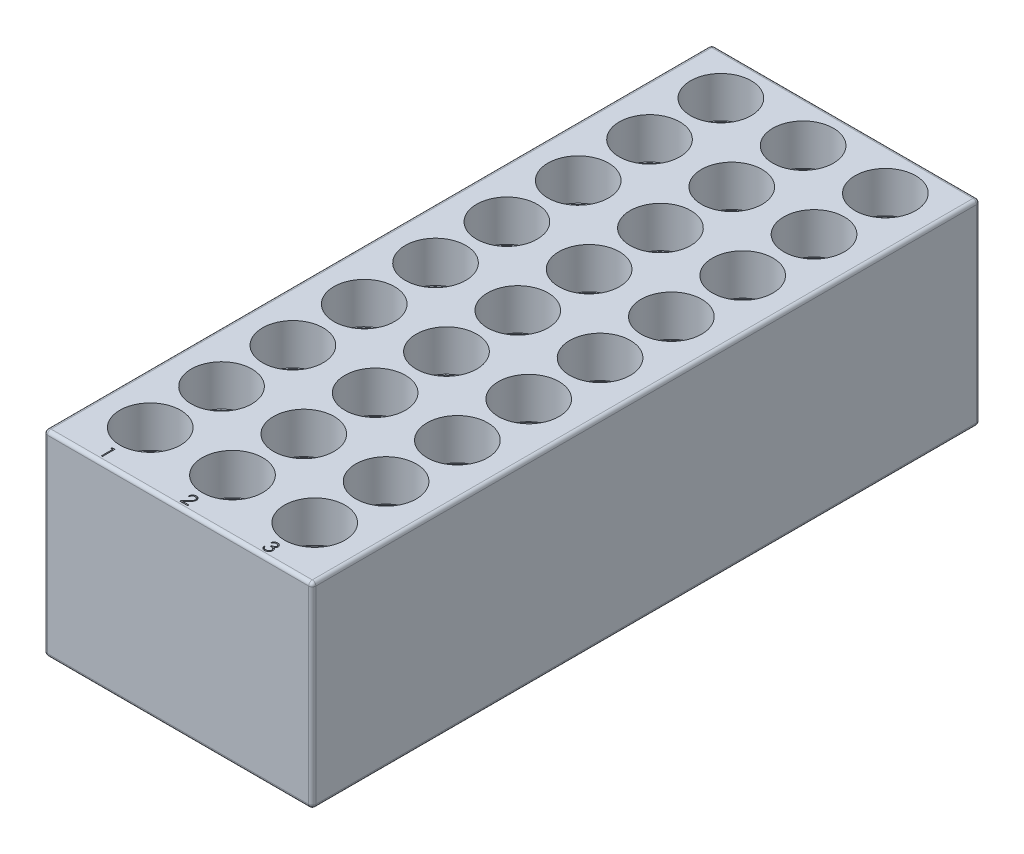
SolidWorks part; units mm, degrees
ref_plane "Front Plane" through (0, 0, 0) normal (0, 0, 1) x (1, 0, 0)
ref_plane "Top Plane" through (0, 0, 0) normal (0, 1, 0) x (1, 0, 0)
ref_plane "Right Plane" through (0, 0, 0) normal (1, 0, 0) x (0, 0, -1)
sketch "Sketch1" plane through (0, 0, 0) normal (0, 1, 0) x (1, 0, 0)
  line L0 (-23.0625, 61.625) -> (-37.625, 61.625) construction
  line L1 (37.625, -93.625) -> (-37.625, -93.625)
  line L2 (37.625, -93.625) -> (37.625, 93.625)
  line L3 (37.625, 93.625) -> (-37.625, 93.625)
  line L4 (-37.625, -93.625) -> (-37.625, 93.625)
  line L5 (37.625, -93.625) -> (-37.625, 93.625) construction
  line L6 (37.625, 93.625) -> (-37.625, -93.625) construction
  line L7 (-23.0625, 81.625) -> (-37.625, 81.625) construction
  line L8 (-23.0625, 81.625) -> (-23.0625, 93.625) construction
  line L9 (23.0625, 81.625) -> (37.625, 81.625) construction
  line L10 (-8.5, 81.625) -> (-23.0625, 81.625) construction
  circle A0 centre (-23.0625, 81.625) radius 8.5
  circle A1 centre (0, 81.625) radius 8.5
  circle A2 centre (23.0625, 81.625) radius 8.5
  circle A6 centre (-23.0625, 61.625) radius 8.5
  circle A7 centre (0, 61.625) radius 8.5
  circle A8 centre (23.0625, 61.625) radius 8.5
  circle A12 centre (-23.0625, 41.625) radius 8.5
  circle A13 centre (0, 41.625) radius 8.5
  circle A14 centre (23.0625, 41.625) radius 8.5
  circle A18 centre (-23.0625, 21.625) radius 8.5
  circle A19 centre (0, 21.625) radius 8.5
  circle A20 centre (23.0625, 21.625) radius 8.5
  circle A24 centre (-23.0625, 1.625) radius 8.5
  circle A25 centre (0, 1.625) radius 8.5
  circle A26 centre (23.0625, 1.625) radius 8.5
  circle A30 centre (-23.0625, -18.375) radius 8.5
  circle A31 centre (0, -18.375) radius 8.5
  circle A32 centre (23.0625, -18.375) radius 8.5
  circle A36 centre (-23.0625, -38.375) radius 8.5
  circle A37 centre (0, -38.375) radius 8.5
  circle A38 centre (23.0625, -38.375) radius 8.5
  circle A42 centre (-23.0625, -58.375) radius 8.5
  circle A43 centre (0, -58.375) radius 8.5
  circle A44 centre (23.0625, -58.375) radius 8.5
  circle A48 centre (-23.0625, -78.375) radius 8.5
  circle A49 centre (0, -78.375) radius 8.5
  circle A50 centre (23.0625, -78.375) radius 8.5
  point P0 (0, 0)
  dimension "D1" = 17
  dimension "D3" = 20
  dimension "D5" = 12
  dimension "D7" = 187.25
  dimension "D9" = 75.25
  dimension "D2" = 3
  dimension "D6" = 9
extrude "Boss-Extrude1" add sketch "Sketch1" along normal blind 50
sketch "Sketch3" plane through (0, 0, 0) normal (0, -1, 0) x (1, 0, 0)
  line L1 (-37.625, 93.625) -> (37.625, 93.625)
  line L2 (-37.625, 93.625) -> (-37.625, -93.625)
  line L3 (-37.625, -93.625) -> (37.625, -93.625)
  line L4 (37.625, 93.625) -> (37.625, -93.625)
extrude "Boss-Extrude2" add sketch "Sketch3" along normal blind 5
sketch "Sketch4" plane through (0, 50, 0) normal (0, 1, 0) x (1, 0, 0)
  text T0 "1               2               3"
  point P1 (0, 0)
  point P2 (0, 0)
  point P3 (0, 0)
shell "Shell3" [suppressed] thickness 0.1
sketch "Sketch5" plane through (0, 0, 0) normal (0, 1, 0) x (1, 0, 0)
  line L4 (-37.625, -93.625) -> (37.625, -93.625)
  line L5 (-37.625, 93.625) -> (-37.625, -93.625)
  line L6 (37.625, 93.625) -> (-37.625, 93.625)
  line L7 (37.625, -93.625) -> (37.625, 93.625)
  line L8 (-37.625, -93.625) -> (37.625, -93.625)
  line L9 (-37.625, 93.625) -> (-37.625, -93.625)
  line L10 (37.625, 93.625) -> (-37.625, 93.625)
  line L11 (37.625, -93.625) -> (37.625, 93.625)
  circle A0 centre (-23.0625, 81.625) radius 8.1
  circle A1 centre (-0.0625, 81.625) radius 8.1
  circle A2 centre (22.9375, 81.625) radius 8.1
  circle A3 centre (-0.0625, 61.625) radius 8.1
  circle A4 centre (22.9375, 61.625) radius 8.1
  circle A5 centre (-0.0625, 41.625) radius 8.1
  circle A6 centre (22.9375, 41.625) radius 8.1
  circle A7 centre (-0.0625, 21.625) radius 8.1
  circle A8 centre (22.9375, 21.625) radius 8.1
  circle A9 centre (-0.0625, 1.625) radius 8.1
  circle A10 centre (22.9375, 1.625) radius 8.1
  circle A11 centre (-0.0625, -18.375) radius 8.1
  circle A12 centre (22.9375, -18.375) radius 8.1
  circle A13 centre (-0.0625, -38.375) radius 8.1
  circle A14 centre (22.9375, -38.375) radius 8.1
  circle A15 centre (-0.0625, -58.375) radius 8.1
  circle A16 centre (22.9375, -58.375) radius 8.1
  circle A17 centre (-0.0625, -78.375) radius 8.1
  circle A18 centre (22.9375, -78.375) radius 8.1
  circle A19 centre (-23.0625, 61.625) radius 8.1
  circle A20 centre (-23.0625, 41.625) radius 8.1
  circle A21 centre (-23.0625, 21.625) radius 8.1
  circle A22 centre (-23.0625, 1.625) radius 8.1
  circle A23 centre (-23.0625, -18.375) radius 8.1
  circle A24 centre (-23.0625, -38.375) radius 8.1
  circle A25 centre (-23.0625, -58.375) radius 8.1
  circle A26 centre (-23.0625, -78.375) radius 8.1
  circle A28 centre (23.0625, 81.625) radius 8.5
  circle A29 centre (23.0625, 81.625) radius 8.5
  circle A30 centre (0, 81.625) radius 8.5
  circle A31 centre (0, 81.625) radius 8.5
  circle A32 centre (-23.0625, 81.625) radius 8.5
  circle A33 centre (-23.0625, 81.625) radius 8.5
  circle A34 centre (23.0625, 61.625) radius 8.5
  circle A35 centre (23.0625, 61.625) radius 8.5
  circle A36 centre (0, 61.625) radius 8.5
  circle A37 centre (0, 61.625) radius 8.5
  circle A38 centre (-23.0625, 61.625) radius 8.5
  circle A39 centre (-23.0625, 61.625) radius 8.5
  circle A40 centre (-23.0625, 21.625) radius 8.5
  circle A41 centre (-23.0625, 21.625) radius 8.5
  circle A42 centre (23.0625, 41.625) radius 8.5
  circle A43 centre (23.0625, 41.625) radius 8.5
  circle A44 centre (0, 41.625) radius 8.5
  circle A45 centre (0, 41.625) radius 8.5
  circle A46 centre (-23.0625, 41.625) radius 8.5
  circle A47 centre (-23.0625, 41.625) radius 8.5
  circle A48 centre (23.0625, 1.625) radius 8.5
  circle A49 centre (23.0625, 1.625) radius 8.5
  circle A50 centre (0, 1.625) radius 8.5
  circle A51 centre (0, 1.625) radius 8.5
  circle A52 centre (-23.0625, 1.625) radius 8.5
  circle A53 centre (-23.0625, 1.625) radius 8.5
  circle A54 centre (23.0625, 21.625) radius 8.5
  circle A55 centre (23.0625, 21.625) radius 8.5
  circle A56 centre (0, 21.625) radius 8.5
  circle A57 centre (0, 21.625) radius 8.5
  circle A58 centre (23.0625, -18.375) radius 8.5
  circle A59 centre (23.0625, -18.375) radius 8.5
  circle A60 centre (0, -18.375) radius 8.5
  circle A61 centre (0, -18.375) radius 8.5
  circle A62 centre (-23.0625, -18.375) radius 8.5
  circle A63 centre (-23.0625, -18.375) radius 8.5
  circle A64 centre (23.0625, -38.375) radius 8.5
  circle A65 centre (23.0625, -38.375) radius 8.5
  circle A66 centre (0, -38.375) radius 8.5
  circle A67 centre (0, -38.375) radius 8.5
  circle A68 centre (-23.0625, -38.375) radius 8.5
  circle A69 centre (-23.0625, -38.375) radius 8.5
  circle A70 centre (0, -78.375) radius 8.5
  circle A71 centre (0, -78.375) radius 8.5
  circle A72 centre (-23.0625, -78.375) radius 8.5
  circle A73 centre (-23.0625, -78.375) radius 8.5
  circle A74 centre (23.0625, -58.375) radius 8.5
  circle A75 centre (23.0625, -58.375) radius 8.5
  circle A76 centre (0, -58.375) radius 8.5
  circle A77 centre (0, -58.375) radius 8.5
  circle A78 centre (-23.0625, -58.375) radius 8.5
  circle A79 centre (-23.0625, -58.375) radius 8.5
  circle A80 centre (23.0625, -78.375) radius 8.5
  circle A81 centre (23.0625, -78.375) radius 8.5
  dimension "D1" = 16.2
  dimension "D5" = 20
  dimension "D6" = 23
  dimension "D2" = 3
  dimension "D3" = 9
  dimension "D4" = 0
  dimension "D7" = 0
  dimension "D8" = 0
  dimension "D9" = 0
  dimension "D11" = 0
  dimension "D12" = 0
  dimension "D13" = 0
  dimension "D14" = 0
  dimension "D15" = 0
  dimension "D16" = 0
  dimension "D17" = 0
  dimension "D18" = 0
  dimension "D19" = 0
  dimension "D20" = 0
  dimension "D21" = 0
  dimension "D22" = 0
  dimension "D23" = 0
  dimension "D24" = 0
  dimension "D25" = 0
  dimension "D26" = 0
  dimension "D27" = 0
  dimension "D28" = 0
  dimension "D29" = 0
  dimension "D30" = 0
  dimension "D31" = 0
  dimension "D32" = 0
  dimension "D33" = 0
  dimension "D34" = 0
extrude "Boss-Extrude4" add sketch "Sketch5" along normal blind 38.5 contours A33 A0
pattern_linear "LPattern1" count 3 spacing 23 along (1, 0, 0) count 9 spacing 20 along (0, 0, 1) of "Boss-Extrude4"
extrude "Cut-Extrude1" cut sketch "Sketch4" against normal blind 0.5
fillet "Fillet1" radius 1 12 edges at (37.625, 22.5, 93.625) (37.625, 22.5, -93.625) (37.625, -5, 0) (37.625, 50, 0) (0, -5, -93.625) (0, 50, -93.625) (0, -5, 93.625) (0, 50, 93.625) (-37.625, -5, 0) (-37.625, 50, 0) (-37.625, 22.5, 93.625) (-37.625, 22.5, -93.625)
